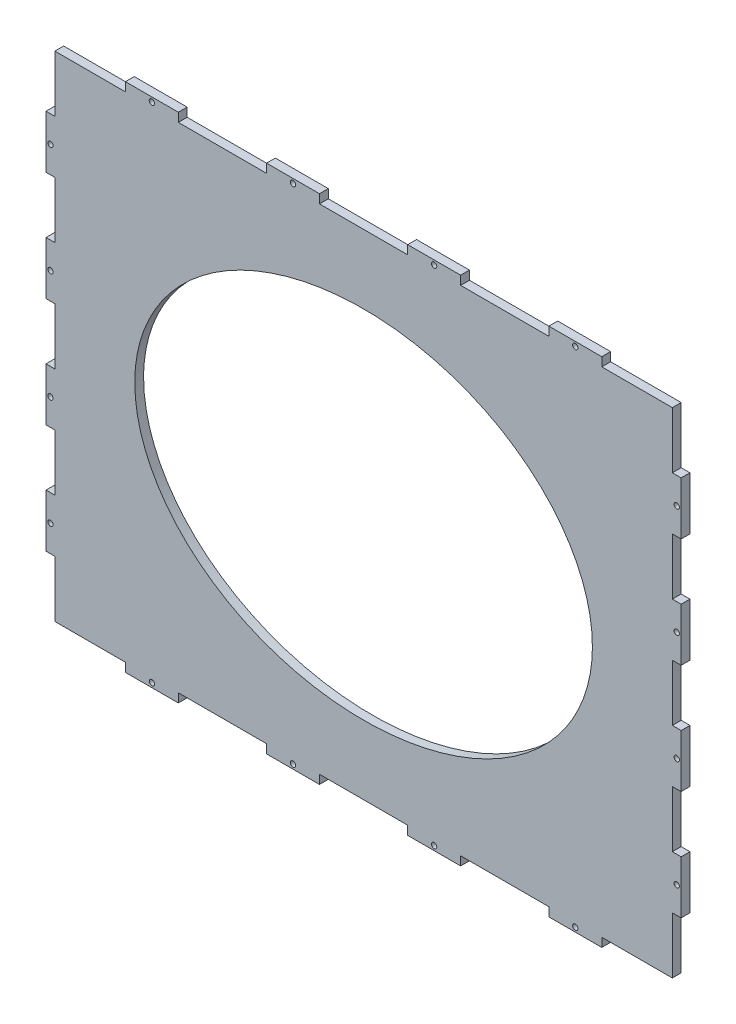
SolidWorks part; units mm, degrees
ref_plane "Front Plane" through (0, 0, 0) normal (0, 0, 1) x (1, 0, 0)
ref_plane "Top Plane" through (0, 0, 0) normal (0, 1, 0) x (1, 0, 0)
ref_plane "Right Plane" through (0, 0, 0) normal (1, 0, 0) x (0, 0, -1)
sketch "Sketch1" plane through (0, 0, 0) normal (0, 0, 1) x (1, 0, 0)
  line L0 (-19.4903, -23.8783) -> (-19.4903, 68.9356) construction
  line L1 (155.5097, -163.8783) -> (115.5097, -163.8783)
  line L2 (155.5097, -163.8783) -> (155.5097, -131.8783)
  line L3 (155.5097, 116.1217) -> (115.5097, 116.1217)
  line L4 (-194.4903, -163.8783) -> (-194.4903, -131.8783)
  line L5 (155.5097, -163.8783) -> (-194.4903, 116.1217) construction
  line L6 (155.5097, 116.1217) -> (-194.4903, -163.8783) construction
  line L7 (-194.4903, 84.1217) -> (-199.4903, 84.1217)
  line L9 (-194.4903, 54.1217) -> (-199.4903, 54.1217)
  line L10 (-199.4903, 84.1217) -> (-199.4903, 54.1217)
  line L11 (-194.4903, 22.1217) -> (-199.4903, 22.1217)
  line L13 (-194.4903, -7.8783) -> (-199.4903, -7.8783)
  line L14 (-199.4903, 22.1217) -> (-199.4903, -7.8783)
  line L15 (-194.4903, -39.8783) -> (-199.4903, -39.8783)
  line L17 (-194.4903, -69.8783) -> (-199.4903, -69.8783)
  line L18 (-199.4903, -39.8783) -> (-199.4903, -69.8783)
  line L19 (-194.4903, -101.8783) -> (-199.4903, -101.8783)
  line L21 (-194.4903, -131.8783) -> (-199.4903, -131.8783)
  line L22 (-199.4903, -101.8783) -> (-199.4903, -131.8783)
  line L24 (-154.4903, 116.1217) -> (-154.4903, 121.1217)
  line L25 (-154.4903, 121.1217) -> (-124.4903, 121.1217)
  line L26 (-124.4903, 116.1217) -> (-124.4903, 121.1217)
  line L28 (-74.4903, 116.1217) -> (-74.4903, 121.1217)
  line L29 (-74.4903, 121.1217) -> (-44.4903, 121.1217)
  line L30 (-44.4903, 116.1217) -> (-44.4903, 121.1217)
  line L32 (5.5097, 116.1217) -> (5.5097, 121.1217)
  line L33 (5.5097, 121.1217) -> (35.5097, 121.1217)
  line L34 (35.5097, 116.1217) -> (35.5097, 121.1217)
  line L36 (85.5097, 116.1217) -> (85.5097, 121.1217)
  line L37 (85.5097, 121.1217) -> (115.5097, 121.1217)
  line L38 (115.5097, 116.1217) -> (115.5097, 121.1217)
  line L39 (-19.4903, -23.8783) -> (-121.2178, -23.8783) construction
  line L40 (155.5097, -131.8783) -> (160.5097, -131.8783)
  line L41 (160.5097, -101.8783) -> (160.5097, -131.8783)
  line L42 (155.5097, -101.8783) -> (160.5097, -101.8783)
  line L43 (160.5097, -39.8783) -> (160.5097, -69.8783)
  line L44 (155.5097, -69.8783) -> (160.5097, -69.8783)
  line L45 (155.5097, -39.8783) -> (160.5097, -39.8783)
  line L46 (155.5097, -7.8783) -> (160.5097, -7.8783)
  line L47 (160.5097, 22.1217) -> (160.5097, -7.8783)
  line L48 (155.5097, 22.1217) -> (160.5097, 22.1217)
  line L49 (155.5097, 54.1217) -> (160.5097, 54.1217)
  line L50 (160.5097, 84.1217) -> (160.5097, 54.1217)
  line L51 (155.5097, 84.1217) -> (160.5097, 84.1217)
  line L52 (115.5097, -163.8783) -> (115.5097, -168.8783)
  line L53 (85.5097, -168.8783) -> (115.5097, -168.8783)
  line L54 (85.5097, -163.8783) -> (85.5097, -168.8783)
  line L55 (35.5097, -163.8783) -> (35.5097, -168.8783)
  line L56 (5.5097, -168.8783) -> (35.5097, -168.8783)
  line L57 (5.5097, -163.8783) -> (5.5097, -168.8783)
  line L58 (-44.4903, -163.8783) -> (-44.4903, -168.8783)
  line L59 (-74.4903, -168.8783) -> (-44.4903, -168.8783)
  line L60 (-74.4903, -163.8783) -> (-74.4903, -168.8783)
  line L61 (-124.4903, -163.8783) -> (-124.4903, -168.8783)
  line L62 (-154.4903, -168.8783) -> (-124.4903, -168.8783)
  line L63 (-154.4903, -163.8783) -> (-154.4903, -168.8783)
  line L64 (-154.4903, 116.1217) -> (-194.4903, 116.1217)
  line L65 (-74.4903, 116.1217) -> (-124.4903, 116.1217)
  line L66 (5.5097, 116.1217) -> (-44.4903, 116.1217)
  line L67 (85.5097, 116.1217) -> (35.5097, 116.1217)
  line L68 (-194.4903, 84.1217) -> (-194.4903, 116.1217)
  line L69 (-194.4903, 22.1217) -> (-194.4903, 54.1217)
  line L70 (-194.4903, -39.8783) -> (-194.4903, -7.8783)
  line L71 (-194.4903, -101.8783) -> (-194.4903, -69.8783)
  line L72 (-154.4903, -163.8783) -> (-194.4903, -163.8783)
  line L73 (-74.4903, -163.8783) -> (-124.4903, -163.8783)
  line L74 (5.5097, -163.8783) -> (-44.4903, -163.8783)
  line L75 (85.5097, -163.8783) -> (35.5097, -163.8783)
  line L76 (155.5097, -101.8783) -> (155.5097, -69.8783)
  line L77 (155.5097, -39.8783) -> (155.5097, -7.8783)
  line L78 (155.5097, 22.1217) -> (155.5097, 54.1217)
  line L79 (155.5097, 84.1217) -> (155.5097, 116.1217)
  line L80 (160.5097, -168.8783) -> (115.5097, -168.8783) construction
  line L81 (160.5097, 121.1217) -> (115.5097, 121.1217) construction
  line L82 (115.5097, 121.1217) -> (115.5097, 116.1217) construction
  line L83 (85.5097, 121.1217) -> (85.5097, 116.1217) construction
  line L84 (5.5097, 121.1217) -> (5.5097, 116.1217) construction
  line L85 (35.5097, 121.1217) -> (35.5097, 116.1217) construction
  line L86 (-199.4903, 116.1217) -> (-199.4903, 84.1217) construction
  line L87 (-154.4903, 121.1217) -> (-154.4903, 116.1217) construction
  line L88 (-124.4903, 121.1217) -> (-124.4903, 116.1217) construction
  line L89 (-74.4903, 121.1217) -> (-74.4903, 116.1217) construction
  line L90 (-44.4903, 121.1217) -> (-44.4903, 116.1217) construction
  line L91 (5.5097, 116.1217) -> (-44.4903, 116.1217) construction
  line L94 (160.5097, 84.1217) -> (160.5097, 74.1217) construction
  line L95 (155.5097, 116.1217) -> (155.5097, 84.1217) construction
  line L96 (155.5097, 84.1217) -> (160.5097, 84.1217) construction
  line L97 (155.5097, 54.1217) -> (160.5097, 54.1217) construction
  line L98 (155.5097, 22.1217) -> (160.5097, 22.1217) construction
  line L99 (155.5097, -7.8783) -> (160.5097, -7.8783) construction
  line L100 (155.5097, -131.8783) -> (160.5097, -131.8783) construction
  line L101 (155.5097, -101.8783) -> (160.5097, -101.8783) construction
  line L102 (155.5097, -69.8783) -> (160.5097, -69.8783) construction
  line L103 (155.5097, -39.8783) -> (160.5097, -39.8783) construction
  circle A0 centre (-139.4903, 118.6217) radius 1.5
  circle A1 centre (-59.4903, 118.6217) radius 1.5
  circle A2 centre (-196.9903, 69.1217) radius 1.5
  circle A3 centre (-196.9903, 7.1217) radius 1.5
  circle A4 centre (158.0097, 7.1217) radius 1.5
  circle A5 centre (158.0097, 69.1217) radius 1.5
  circle A6 centre (100.5097, 118.6217) radius 1.5
  circle A7 centre (20.5097, 118.6217) radius 1.5
  circle A8 centre (158.0097, -54.8783) radius 1.5
  circle A9 centre (158.0097, -116.8783) radius 1.5
  circle A10 centre (100.5097, -166.3783) radius 1.5
  circle A11 centre (20.5097, -166.3783) radius 1.5
  circle A12 centre (-59.4903, -166.3783) radius 1.5
  circle A13 centre (-139.4903, -166.3783) radius 1.5
  circle A14 centre (-196.9903, -54.8783) radius 1.5
  circle A15 centre (-196.9903, -116.8783) radius 1.5
  ellipse E0 centre (-19.4903, -23.8783) end of major axis (-149.1863, -23.8783) minor radius 100.9627
  point P40 (-196.9903, 22.1217)
  point P53 (158.0097, 22.1217)
  point P59 (-74.4903, 118.6217)
  point P60 (35.5097, 118.6217)
  point P65 (35.5097, -166.3783)
  point P73 (-74.4903, -166.3783)
  point P136 (0, 0)
  dimension "D1" = 2.5
  dimension "D2" = 15
  dimension "D4" = 15
  dimension "D6" = 2.5
  dimension "D7" = 2.5
  dimension "D8" = 15
  dimension "D3" = 2.5
  dimension "D5" = 15
extrude "Boss-Extrude1" add sketch "Sketch1" along normal blind 5
